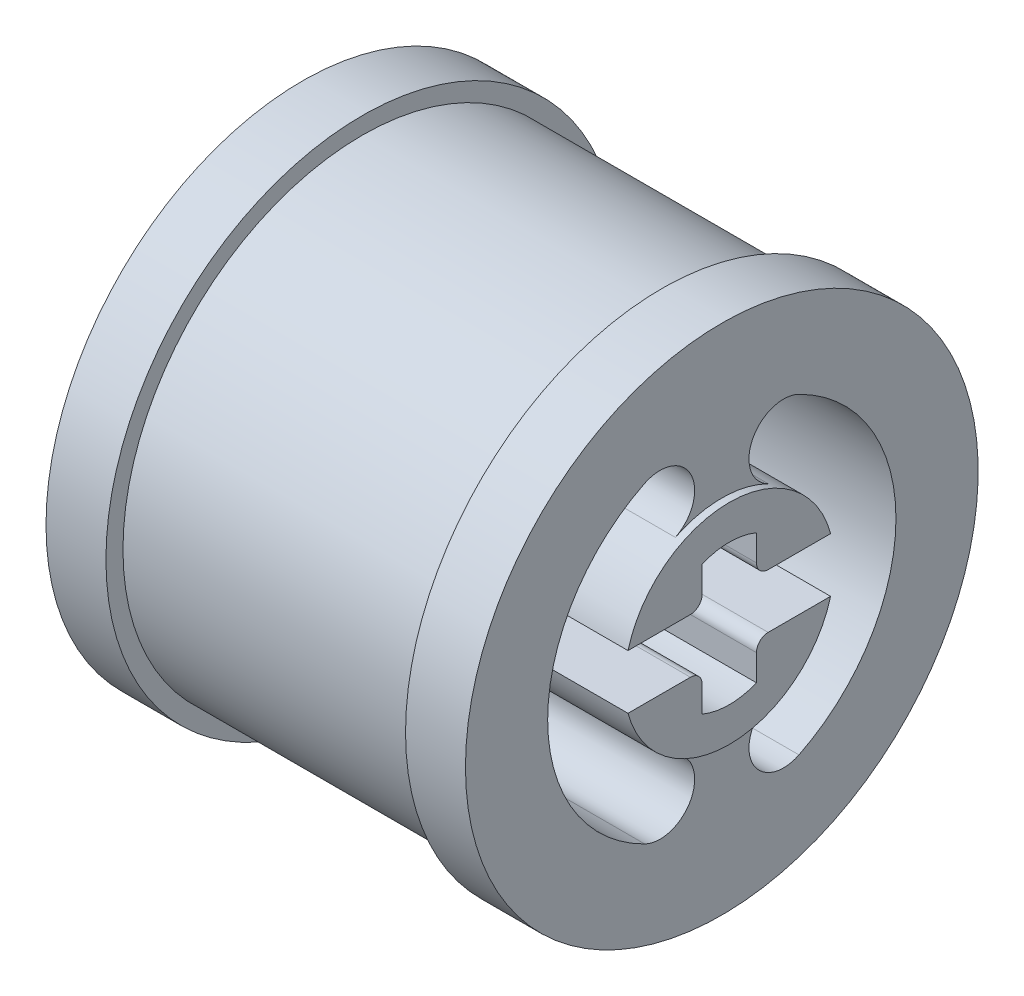
SolidWorks part; units mm, degrees
material "PW40:30:C1:0:1:2:Sc:3:Re:17:"
ref_plane "Front" through (0, 0, 0) normal (0, 0, 1) x (1, 0, 0)
ref_plane "Top" through (0, 0, 0) normal (0, 1, 0) x (1, 0, 0)
ref_plane "Right" through (0, 0, 0) normal (1, 0, 0) x (0, 0, -1)
sketch "Sketch1" plane through (0, 0, 0) normal (0, 0, 1) x (1, 0, 0)
  line L0 (0, 0) -> (96.5008, 0) construction
  line L1 (7.112, 0) -> (7.112, 8.6932)
  line L2 (3.556, 8.1153) -> (5.08, 8.1153)
  line L3 (5.08, 8.6932) -> (7.112, 8.6932)
  line L4 (3.556, 8.1153) -> (0, 8.1153)
  line L5 (0, 8.1153) -> (0, 0)
  line L6 (0, 0) -> (7.112, 0)
  line L7 (0, 0) -> (0, 45.3297) construction
  line L8 (5.08, 8.1153) -> (5.08, 8.6932)
  dimension "D1" = 2.032
  dimension "D2" = 14.224
  dimension "D3" = 7.112
  dimension "D4" = 17.3863
  dimension "D5" = 16.2306
revolve "Base-Revolve" add sketch "Sketch1" angle 360 about L0
sketch "Sketch2" plane through (7.112, 0, 0) normal (1, 0, 0) x (0, 0, -1)
  circle A0 centre (0, 0) radius 3.556
  dimension "D1" = 7.112
extrude "Boss-Extrude1" add sketch "Sketch2" along normal blind 0.254
sketch "Sketch3" plane through (7.112, 0, 0) normal (1, 0, 0) x (0, 0, -1)
  line L0 (-0.9207, 0) -> (-0.9208, -8.022) construction
  line L1 (0, 0) -> (-9.3112, 0) construction
  line L2 (0, 0) -> (0, -9.0452) construction
  arc A0 (2.6159, -5.2945) -> (2.6159, 5.2945) centre (0, 0) ccw
  circle A1 centre (0, 0) radius 3.556 construction
  arc A2 (1.5751, -3.1881) -> (1.5751, 3.1881) centre (0, 0) ccw
  arc A3 (-2.6159, -5.2945) -> (-1.5751, -3.1881) centre (-2.0955, -4.2413) ccw
  arc A4 (-2.6159, 5.2945) -> (-1.5751, 3.1881) centre (-2.0955, 4.2413) cw
  arc A5 (2.6159, 5.2945) -> (1.5751, 3.1881) centre (2.0955, 4.2413) ccw
  arc A6 (2.6159, -5.2945) -> (1.5751, -3.1881) centre (2.0955, -4.2413) cw
  arc A7 (-1.5751, 3.1881) -> (-1.5751, -3.1881) centre (0, 0) ccw
  arc A8 (-2.6159, 5.2945) -> (-2.6159, -5.2945) centre (0, 0) ccw
  dimension "D1" = 11.811
  dimension "D2" = 0.9207
extrude "Cut-Extrude1" cut sketch "Sketch3" against normal through all
sketch "Sketch4" plane through (7.366, 0, 0) normal (1, 0, 0) x (0, 0, -1)
  line L0 (0, 0) -> (9.4749, 0) construction
  line L1 (0, 0) -> (0, 9.2089) construction
  line L2 (3.4347, 0.9207) -> (0.9207, 0.9208)
  line L3 (0.9207, 0.9208) -> (0.9207, 2.2029)
  line L4 (-3.4347, 0.9207) -> (-0.9207, 0.9208)
  line L5 (-0.9207, 0.9208) -> (-0.9207, 2.2029)
  line L6 (3.4347, -0.9207) -> (0.9207, -0.9208)
  line L7 (0.9207, -0.9208) -> (0.9207, -2.2029)
  line L8 (-0.9207, -0.9208) -> (-0.9207, -2.2029)
  line L9 (-3.4347, -0.9207) -> (-0.9207, -0.9208)
  circle A0 centre (0, 0) radius 3.556 construction
  arc A1 (0.9207, 2.2029) -> (-0.9207, 2.2029) centre (0, 0) ccw
  arc A2 (2.6159, 5.2945) -> (1.5751, 3.1881) centre (2.0955, 4.2413) ccw construction
  arc A3 (0.9207, -2.2029) -> (-0.9207, -2.2029) centre (0, 0) cw
  arc A4 (3.4347, -0.9207) -> (3.4347, 0.9207) centre (0, 0) ccw
  arc A5 (-3.4347, 0.9207) -> (-3.4347, -0.9207) centre (0, 0) ccw
  dimension "D1" = 4.7752
  dimension "D2" = 1.8415
extrude "Cut-Extrude2" cut sketch "Sketch4" against normal through all
fillet "Fillet1" radius 0.3969 4 edges at (3.683, -0.9208, -0.9207) (3.683, -0.9208, 0.9207) (3.683, 0.9208, 0.9207) (3.683, 0.9208, -0.9207)
mirror "Boss-Mirror1" of bodies 104
